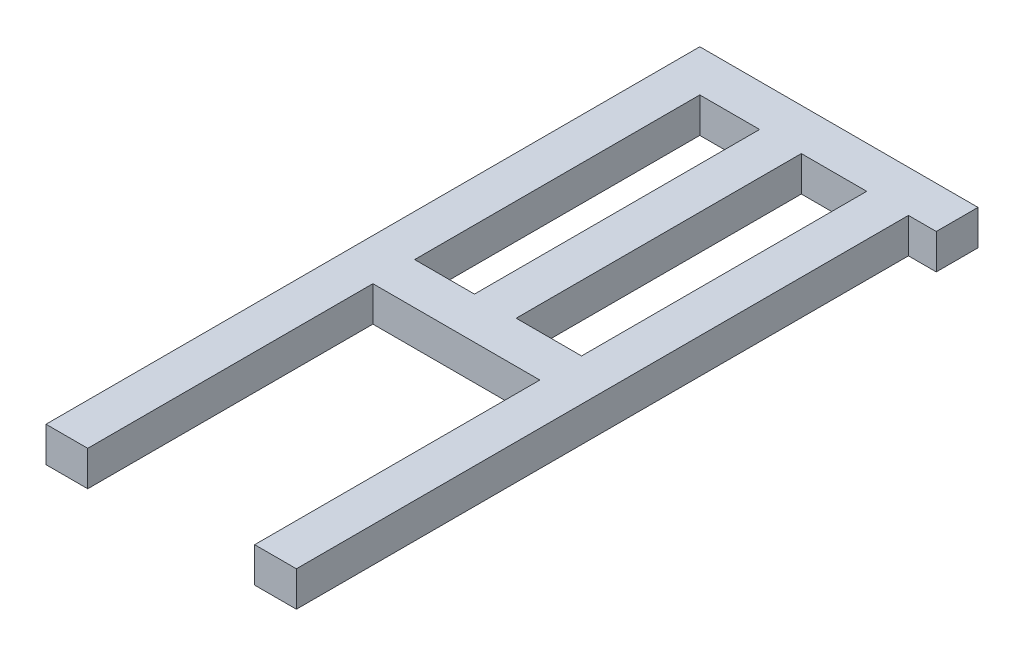
SolidWorks part; units mm, degrees
ref_plane "Plan de face" through (0, 0, 0) normal (0, 0, 1) x (1, 0, 0)
ref_plane "Plan de dessus" through (0, 0, 0) normal (0, 1, 0) x (1, 0, 0)
ref_plane "Plan de droite" through (0, 0, 0) normal (1, 0, 0) x (0, 0, -1)
sketch "Esquisse1" plane through (0, 0, 0) normal (0, 0, 1) x (1, 0, 0)
  line L0 (0, 0) -> (75, 0)
  line L1 (0, 0) -> (0, 63)
  line L2 (75, 0) -> (75, 63)
  line L3 (0, 63) -> (75, 63)
  dimension "D1" = 63
extrude "Boss.-Extru.1" add sketch "Esquisse1" along normal blind 1100
pattern_linear "Répétition linéaire2" count 2 spacing 375 along (-1, 0, 0) of "Boss.-Extru.1"
sketch "Esquisse3" plane through (0, 0, 0) normal (0, 0, 1) x (1, 0, 0)
  line L0 (-117.5, 0) -> (-117.5, 63)
  line L1 (-117.5, 0) -> (-192.5, 0)
  line L2 (-117.5, 63) -> (-192.5, 63)
  line L3 (-192.5, 0) -> (-192.5, 63)
  line L4 (-375, 63) -> (-375, 0) construction
  dimension "D1" = 63
  dimension "D2" = 75
  dimension "D3" = 182.5
extrude "Boss.-Extru.2" add sketch "Esquisse3" along normal blind 512.5 separate body
sketch "Esquisse4" plane through (-192.5, 0, 0) normal (-1, 0, 0) x (0, 0, 1)
  line L0 (512.5, 0) -> (512.5, 63)
  line L1 (512.5, 0) -> (587.5, 0)
  line L2 (512.5, 63) -> (587.5, 63)
  line L3 (587.5, 0) -> (587.5, 63)
  dimension "D1" = 75
extrude "Boss.-Extru.3" add sketch "Esquisse4" along normal up to next (182.5 mm away) and the other way up to next (192.5 mm away)
sketch "Esquisse5" plane through (-375, 0, 0) normal (-1, 0, 0) x (0, 0, 1)
  line L0 (0, 63) -> (0, 0)
  line L1 (0, 63) -> (-75, 63)
  line L2 (0, 0) -> (-75, 0)
  line L3 (-75, 63) -> (-75, 0)
  line L4 (1100, 63) -> (1100, 0)
  line M1 (0, 63) -> (0, 0)
extrude "Boss.-Extru.4" add sketch "Esquisse5" against normal blind 500 contours L1 L3 L2 M1
